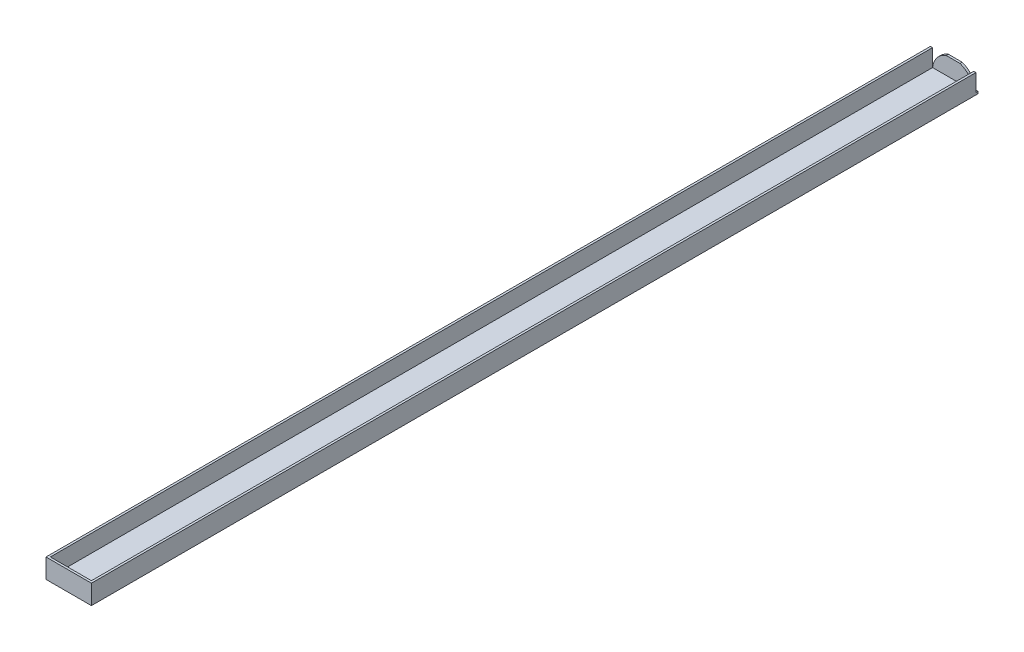
SolidWorks part; units mm, degrees
ref_plane "Front Plane" through (0, 0, 0) normal (0, 0, 1) x (1, 0, 0)
ref_plane "Top Plane" through (0, 0, 0) normal (0, 1, 0) x (1, 0, 0)
ref_plane "Right Plane" through (0, 0, 0) normal (1, 0, 0) x (0, 0, -1)
sketch "Sketch1" plane through (0, 0, 0) normal (0, 0, 1) x (1, 0, 0)
  line L1 (0, 0) -> (21, 0)
  line L2 (0, 0) -> (0, -9)
  line L3 (0, -9) -> (21, -9)
  line L4 (21, 0) -> (21, -9)
  dimension "D1" = 21
  dimension "D2" = 9
extrude "Boss-Extrude1" add sketch "Sketch1" along normal blind 410
sketch "Sketch2" plane through (0, 0, 0) normal (0, 1, 0) x (1, 0, 0)
  line L0 (21, -410) -> (0, -410) construction
  line L1 (1, -1) -> (20, -1)
  line L2 (1, -1) -> (1, -409)
  line L3 (1, -409) -> (20, -409)
  line L4 (20, -1) -> (20, -409)
  line L5 (0, -410) -> (0, 0) construction
  line L6 (21, -410) -> (21, 0) construction
  line L7 (21, 0) -> (0, 0) construction
  dimension "D1" = 1
  dimension "D2" = 1
  dimension "D3" = 1
  dimension "D4" = 1
extrude "Cut-Extrude1" cut sketch "Sketch2" against normal blind 8
sketch "Sketch4" plane through (0, 0, 0) normal (0, 0, -1) x (-1, 0, 0)
  line L0 (-20, -8) -> (-20, -0.5402) construction
  line L1 (-21, -9) -> (-21, 0) construction
  line L2 (0, -9) -> (-21, -9) construction
  line L3 (-20, -8.0615) -> (-20, 0)
  line L4 (-21, 0) -> (0, 0) construction
  line L5 (-20, 0) -> (-13.6829, 0)
  line L6 (-10.5, -9) -> (-10.5, -6.5837) construction
  line L7 (-1, 0) -> (-7.3171, 0)
  line L8 (-1, -8.0615) -> (-1, 0)
  arc A0 (-20, -8.0615) -> (-13.6829, 0) centre (-10.5, -9) cw
  arc A1 (-1, -8.0615) -> (-7.3171, 0) centre (-10.5, -9) ccw
  dimension "D1" = 1
  dimension "D2" = 1
extrude "Cut-Extrude2" cut sketch "Sketch4" against normal blind 8
sketch "Sketch5" plane through (21, 0, 0) normal (1, 0, 0) x (0, 0, -1)
  line L0 (-410, -9) -> (0, -9) construction
  line L1 (0, 0) -> (-1, 0)
  line L2 (0, 0) -> (0, -8)
  line L3 (0, -8) -> (-1, -8)
  line L4 (-1, 0) -> (-1, -8)
  dimension "D1" = 1
  dimension "D2" = 1
extrude "Cut-Extrude3" cut sketch "Sketch5" against normal up to surface (1 mm away) up to face at (20, -5.3538, 139)
sketch "Sketch6" plane through (0, 0, 0) normal (-1, 0, 0) x (0, 0, 1)
  line L0 (410, -9) -> (0, -9) construction
  line L1 (0, 0) -> (1, 0)
  line L2 (0, 0) -> (0, -8)
  line L3 (0, -8) -> (1, -8)
  line L4 (1, 0) -> (1, -8)
  dimension "D1" = 1
  dimension "D2" = 1
extrude "Cut-Extrude4" cut sketch "Sketch6" against normal up to surface (1 mm away) up to face at (1, -5.3538, 139)
